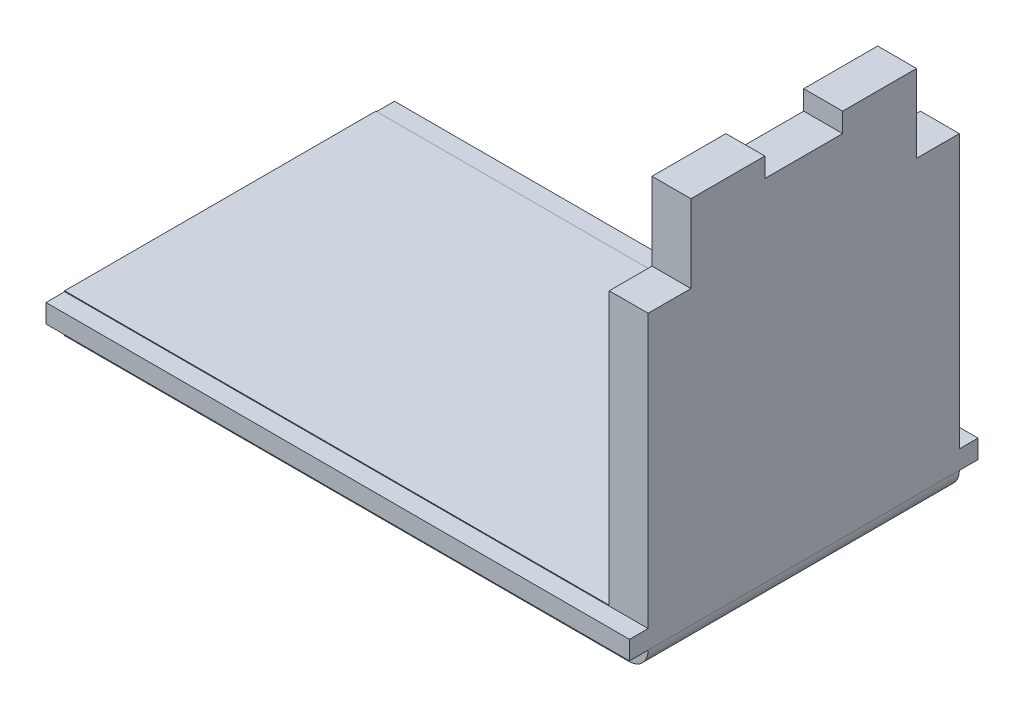
SolidWorks part; units mm, degrees
ref_plane "Front Plane" through (0, 0, 0) normal (0, 0, 1) x (1, 0, 0)
ref_plane "Top Plane" through (0, 0, 0) normal (0, 1, 0) x (1, 0, 0)
ref_plane "Right Plane" through (0, 0, 0) normal (1, 0, 0) x (0, 0, -1)
sketch "Sketch1" plane through (0, 0, 0) normal (0, 0, 1) x (1, 0, 0)
  line L0 (0, 0) -> (0, 8.9196) construction
  line L1 (-80, 0) -> (70, 0)
  line L2 (70, 0) -> (70, 100)
  line L3 (-80, 10) -> (60, 10)
  line L4 (60, 10) -> (60, 100)
  line L5 (-80, 0) -> (-80, 10)
  line L6 (70, 100) -> (60, 100)
  dimension "D1" = 80
  dimension "D2" = 150
  dimension "D3" = 100
  dimension "D4" = 10
extrude "Boss-Extrude1" add sketch "Sketch1" along normal blind 80
sketch "Sketch2" plane through (70, 0, 0) normal (1, 0, 0) x (0, 0, -1)
  line L1 (-80, 0) -> (-80, 100) construction
  line L4 (-80, 9.8) -> (-80, 5)
  line L5 (-80, 5) -> (-84.8, 5)
  line L6 (-84.8, 5) -> (-84.8, 9.8)
  line L7 (-84.8, 9.8) -> (-80, 9.8)
  line L8 (-40, 0) -> (-40, 100) construction
  line L9 (-80, 0) -> (0, 0) construction
  line L10 (-80, 100) -> (0, 100) construction
  line L11 (4.8, 5) -> (4.8, 9.8)
  line L12 (0, 5) -> (4.8, 5)
  line L13 (0, 9.8) -> (0, 5)
  line L14 (4.8, 9.8) -> (0, 9.8)
  dimension "D1" = 4.8
  dimension "D2" = 5
extrude "Boss-Extrude2" add sketch "Sketch2" against normal up to surface (150 mm away) up to face at (-80, 5, 40)
sketch "Sketch3" plane through (70, 0, 0) normal (1, 0, 0) x (0, 0, -1)
  line L0 (-40, 100) -> (-50, 100)
  line L1 (-80, 9.8) -> (-80, 100) construction
  line L2 (-80, 80) -> (-69, 80)
  line L3 (-69, 80) -> (-69, 100)
  line L4 (-80, 100) -> (0, 100) construction
  line L5 (-80, 0) -> (0, 0) construction
  line L6 (-80, 80) -> (-80, 100)
  line L7 (-80, 100) -> (-69, 100)
  line L8 (-40, 100) -> (-40, 0) construction
  line L9 (0, 100) -> (-11, 100)
  line L10 (0, 80) -> (0, 100)
  line L11 (0, 80) -> (-11, 80)
  line L12 (-11, 80) -> (-11, 100)
  line L13 (-50, 100) -> (-50, 95)
  line L14 (-50, 95) -> (-30, 95)
  line L15 (-30, 95) -> (-30, 100)
  line L16 (-30, 100) -> (-40, 100)
  dimension "D1" = 80
  dimension "D2" = 11
  dimension "D3" = 10
  dimension "D4" = 5
extrude "Cut-Extrude1" cut sketch "Sketch3" against normal through all
fillet "Fillet1" radius 5 1 edges at (70, 0, 40)
